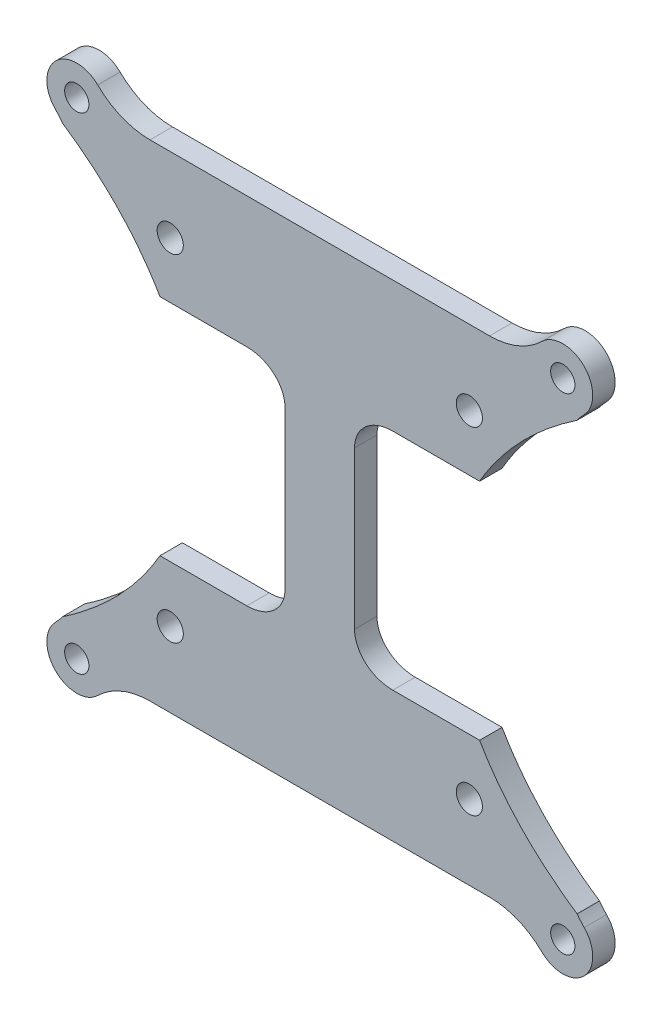
SolidWorks part; units mm, degrees
material "ABS"
ref_plane "Спереди" through (0, 0, 0) normal (0, 0, 1) x (1, 0, 0)
ref_plane "Сверху" through (0, 0, 0) normal (0, 1, 0) x (1, 0, 0)
ref_plane "Справа" through (0, 0, 0) normal (1, 0, 0) x (0, 0, -1)
sketch "Эскиз1" plane through (0, 0, 0) normal (0, 0, 1) x (1, 0, 0)
  line L1 (-32.5, -32.5) -> (32.5, -32.5)
  line L2 (-32.5, -32.5) -> (-32.5, 32.5)
  line L3 (-32.5, 32.5) -> (32.5, 32.5)
  line L4 (32.5, -32.5) -> (32.5, 32.5)
  line L5 (-32.5, -32.5) -> (32.5, 32.5) construction
  line L6 (-32.5, 32.5) -> (32.5, -32.5) construction
  circle A0 centre (-32.5, 32.5) radius 1.625
  arc A1 (-28.5, 32.5) -> (-32.5, 28.5) centre (-32.5, 32.5) ccw
  circle A2 centre (32.5, 32.5) radius 1.625
  arc A3 (32.5, 28.5) -> (28.5, 32.5) centre (32.5, 32.5) ccw
  circle A4 centre (32.5, -32.5) radius 1.625
  arc A5 (28.5, -32.5) -> (32.5, -28.5) centre (32.5, -32.5) ccw
  circle A6 centre (-32.5, -32.5) radius 1.625
  arc A7 (-32.5, -28.5) -> (-28.5, -32.5) centre (-32.5, -32.5) ccw
  point P0 (0, 0)
  point P20 (0, 0)
  dimension "D2" = 3.25
  dimension "D3" = 8
  dimension "D1" = 65
  dimension "D4" = 4
extrude "Бобышка-Вытянуть1" add sketch "Эскиз1" along normal blind 3 contours A6 L1 A4 L4 A2 L3 A0 L2 | L3 A1 L2 A0 | L4 A3 L3 A2 | L1 A5 L4 A4 | L2 A7 L1 A6
fillet "Скругление1" radius 10 8 edges at (-28.5, -32.5, 1.5) (-32.5, -28.5, 1.5) (-28.5, 32.5, 1.5) (-32.5, 28.5, 1.5) (28.5, 32.5, 1.5) (32.5, 28.5, 1.5) (32.5, -28.5, 1.5) (28.5, -32.5, 1.5)
sketch "Эскиз2" plane through (0, 0, 0) normal (0, 0, -1) x (-1, 0, 0)
  line L0 (0, 32.5) -> (0, -32.5) construction
  line L1 (22.702, 32.5) -> (-22.702, 32.5) construction
  line L2 (22.702, -32.5) -> (-22.702, -32.5) construction
  line L3 (-32.5, 22.5) -> (32.5, 22.5) construction
  line L4 (-32.5, -22.702) -> (-32.5, 22.702) construction
  line L5 (32.5, -22.702) -> (32.5, 22.702) construction
  line L6 (-32.5, 0) -> (32.5, 0) construction
  circle A0 centre (-20, 22.5) radius 1.75
  circle A1 centre (20, 22.5) radius 1.75
  circle A2 centre (20, -22.5) radius 1.75
  circle A3 centre (-20, -22.5) radius 1.75
  dimension "D1" = 3.5
  dimension "D2" = 20
  dimension "D3" = 10
extrude "Вырез-Вытянуть1" cut sketch "Эскиз2" against normal blind 10
sketch "Эскиз3" plane through (0, 0, 0) normal (0, 0, -1) x (-1, 0, 0)
  line L0 (40.1734, -19.1012) -> (40.1734, -10.8255)
  line L1 (38.7591, -18.1012) -> (38.7591, -11.8255)
  line L2 (38.7591, -18.1012) -> (40.1734, -19.1012)
  line L3 (40.1734, -10.8255) -> (38.7591, -11.8255)
  line L4 (81.8151, -12.8801) -> (82.0001, -12.7701)
  line L5 (81.993, 12.7739) -> (81.7613, 12.9159)
  line L6 (75.9847, -15.2389) -> (79.1335, -15.9875)
  line L7 (79.1811, 15.9349) -> (75.694, 15.2742)
  line L8 (80.0623, 15.5421) -> (80.9227, 13.8292)
  line L9 (80.9227, -13.8292) -> (80.0272, -15.612)
  line L10 (23.1698, 12) -> (9.7678, 12)
  line L11 (23.1698, -12) -> (9.7678, -12)
  line L12 (68.4576, 34.4102) -> (68.4576, 33.9999)
  line L13 (68.4576, -33.9999) -> (68.4575, -34.4102)
  line L14 (23.5994, 5.6485) -> (23.5994, -5.6485)
  line L15 (7.6464, 10.5) -> (7.6464, -10.5)
  line L16 (7.6464, 10.5) -> (7.6464, -10.5)
  line L17 (23.5994, 5.6485) -> (23.5994, -5.6485)
  line L18 (68.4576, -33.9999) -> (68.4575, -34.4102)
  line L19 (68.4576, 34.4102) -> (68.4576, 33.9999)
  line L20 (23.1698, -12) -> (9.7678, -12)
  line L21 (23.1698, 12) -> (9.7678, 12)
  line L22 (80.9227, -13.8292) -> (80.0272, -15.612)
  line L23 (80.0623, 15.5421) -> (80.9227, 13.8292)
  line L24 (79.1811, 15.9349) -> (75.694, 15.2742)
  line L25 (75.9847, -15.2389) -> (79.1335, -15.9875)
  line L26 (81.993, 12.7739) -> (81.7613, 12.9159)
  line L27 (81.8151, -12.8801) -> (82.0001, -12.7701)
  line L28 (40.1734, -10.8255) -> (38.7591, -11.8255)
  line L29 (38.7591, -18.1012) -> (40.1734, -19.1012)
  line L30 (38.7591, -18.1012) -> (38.7591, -11.8255)
  line L31 (40.1734, -19.1012) -> (40.1734, -10.8255)
  line L32 (-40.1734, 19.1012) -> (-40.1734, 10.8255)
  line L33 (-38.7591, 18.1012) -> (-38.7591, 11.8255)
  line L34 (-38.7591, 18.1012) -> (-40.1734, 19.1012)
  line L35 (-40.1734, 10.8255) -> (-38.7591, 11.8255)
  line L36 (-81.8151, 12.8801) -> (-82.0001, 12.7701)
  line L37 (-81.993, -12.7739) -> (-81.7613, -12.9159)
  line L38 (-75.9847, 15.2389) -> (-79.1335, 15.9875)
  line L39 (-79.1811, -15.9349) -> (-75.694, -15.2742)
  line L40 (-80.0623, -15.5421) -> (-80.9227, -13.8292)
  line L41 (-80.9227, 13.8292) -> (-80.0272, 15.612)
  line L42 (-23.1698, -12) -> (-9.7678, -12)
  line L43 (-23.1698, 12) -> (-9.7678, 12)
  line L44 (-68.4576, -34.4102) -> (-68.4576, -33.9999)
  line L45 (-68.4576, 33.9999) -> (-68.4576, 34.4102)
  line L46 (-23.5994, -5.6485) -> (-23.5994, 5.6485)
  line L47 (-7.6464, -10.5) -> (-7.6464, 10.5)
  line L48 (-7.6464, -10.5) -> (-7.6464, 10.5)
  line L49 (-23.5994, -5.6485) -> (-23.5994, 5.6485)
  line L50 (-68.4576, 33.9999) -> (-68.4576, 34.4102)
  line L51 (-68.4576, -34.4102) -> (-68.4576, -33.9999)
  line L52 (-23.1698, 12) -> (-9.7678, 12)
  line L53 (-23.1698, -12) -> (-9.7678, -12)
  line L54 (-80.9227, 13.8292) -> (-80.0272, 15.612)
  line L55 (-80.0623, -15.5421) -> (-80.9227, -13.8292)
  line L56 (-79.1811, -15.9349) -> (-75.694, -15.2742)
  line L57 (-75.9847, 15.2389) -> (-79.1335, 15.9875)
  line L58 (-81.993, -12.7739) -> (-81.7613, -12.9159)
  line L59 (-81.8151, 12.8801) -> (-82.0001, 12.7701)
  line L60 (-40.1734, 10.8255) -> (-38.7591, 11.8255)
  line L61 (-38.7591, 18.1012) -> (-40.1734, 19.1012)
  line L62 (-38.7591, 18.1012) -> (-38.7591, 11.8255)
  line L63 (-40.1734, 19.1012) -> (-40.1734, 10.8255)
  line L64 (-21.3752, 15) -> (-9.7678, 15)
  line L65 (-4.6464, -10.5) -> (-4.6464, 10.5)
  line L66 (-21.3752, -15) -> (-9.7678, -15)
  line L67 (-71.4576, -34.4101) -> (-71.4576, -31.1169)
  line L68 (-26.5994, -5.2847) -> (-26.5994, 5.2847)
  line L69 (-71.4576, 31.1169) -> (-71.4576, 34.4102)
  line L70 (21.3752, 15) -> (9.7678, 15)
  line L71 (4.6464, 10.5) -> (4.6464, -10.5)
  line L72 (21.3752, -15) -> (9.7678, -15)
  line L73 (71.4587, -31.117) -> (71.4575, -34.4505)
  line L74 (26.5994, 5.2847) -> (26.5994, -5.2847)
  line L75 (71.4576, 34.4109) -> (71.4577, 31.1169)
  spline S0 degree 3 poles (10.4749, -7.5) (10.4749, -3.5) (16.1317, -3.5) (16.1317, -7.5) (16.1317, -11.5) (10.4749, -11.5) (10.4749, -7.5) (10.4749, -3.5) (16.1317, -3.5) knots -0.5 0 0 0 0.5 0.5 0.5 1 1 1 1.5 1.5 1.5 weights 1 0.333333 0.333333 1 0.333333 0.333333 1 0.333333 0.333333 only from (10.4749, -7.5) to (10.4749, -7.5)
  spline S1 degree 3 poles (10.4749, 7.5) (10.4749, 11.5) (16.1317, 11.5) (16.1317, 7.5) (16.1317, 3.5) (10.4749, 3.5) (10.4749, 7.5) (10.4749, 11.5) (16.1317, 11.5) knots -0.5 0 0 0 0.5 0.5 0.5 1 1 1 1.5 1.5 1.5 weights 1 0.333333 0.333333 1 0.333333 0.333333 1 0.333333 0.333333 only from (10.4749, 7.5) to (10.4749, 7.5)
  spline S2 degree 3 poles (75.2786, -15.2354) (75.5104, -15.1829) (75.7539, -15.1841) (75.9847, -15.2389) knots 0 0 0 0 1 1 1 1 weights 1 0.966708 0.966708 1
  spline S3 degree 3 poles (-1611.9841, -2490.4248) (107.8063, 15.4248) (78.9871, -16.9374) (81.0411, -13.6256) (81.1175, -13.5185) (81.2068, -13.4081) (81.3058, -13.2991) (81.4203, -13.1863) (81.5604, -13.0632) (86.0077, -9.7973) (-8.3315, -82.6851) (1958.2049, 2327.5554) knots -7.34165 -7.34165 -7.34165 -7.34165 0.084221 0.176281 0.276186 0.383927 0.499481 0.611478 0.749788 0.924174 8.950699 8.950699 8.950699 8.950699 only from (80.9227, -13.8292) to (81.8151, -12.8801)
  spline S4 degree 3 poles (80.0272, -15.612) (79.8643, -15.9364) (79.5225, -16.08) (79.1335, -15.9875) knots 0 0 0 0 1 1 1 1 weights 1 0.8715 0.8715 1
  spline S5 degree 3 poles (75.694, 15.2742) (75.4864, 15.2349) (75.2715, 15.2378) (75.0662, 15.2828) knots 0 0 0 0 1 1 1 1 weights 1 0.97382 0.97382 1
  spline S6 degree 3 poles (79.1811, 15.9349) (79.5679, 16.0082) (79.9033, 15.8587) (80.0623, 15.5421) knots 0 0 0 0 1 1 1 1 weights 1 0.875797 0.875797 1
  spline S7 degree 3 poles (-1937.5466, -2205.5697) (231.9437, 201.1466) (98.3102, -0.4929) (81.5125, 13.1046) (81.3962, 13.2091) (81.2675, 13.3383) (81.137, 13.4904) (77.3927, 18.8363) (129.5432, -17.5929) (-2030.1695, 2144.6881) knots -51.132511 -51.132511 -51.132511 -51.132511 0.124537 0.249858 0.374039 0.498828 0.686618 0.853684 14.255317 14.255317 14.255317 14.255317 only from (81.7613, 12.9159) to (80.9227, 13.8292)
  spline S8 degree 3 poles (3061.2547, -241.2689) (42.8141, -24.9242) (69.0039, -30.7252) (68.4405, -34.6081) (68.4142, -34.7204) (68.3493, -34.9029) (68.2007, -35.1493) (67.9533, -35.395) (67.6517, -35.5947) (67.3374, -35.7342) (66.9897, -35.8321) (66.6982, -35.8734) (59.3585, -36.2144) (52.2357, -1.2696) (37.4507, -3035.645) knots -3.843288 -3.843288 -3.843288 -3.843288 0.033193 0.06659 0.100333 0.149309 0.261141 0.386702 0.497425 0.623884 0.731384 0.860481 0.9194 8.126573 8.126573 8.126573 8.126573 only from (68.4575, -34.4102) to (66.2132, -35.8754)
  spline S9 degree 3 poles (2878.0258, 1077.9449) (41.8351, -70.8926) (52.2555, 35.5569) (66.4941, 35.8853) (66.7631, 35.8695) (67.1233, 35.8008) (67.4532, 35.6896) (67.7786, 35.5205) (68.0573, 35.3049) (68.248, 35.0751) (68.356, 34.8784) (68.4144, 34.7238) (70.0481, 27.3563) (-5.7355, 46.2982) (1192.6861, -2746.0805) knots -14.151772 -14.151772 -14.151772 -14.151772 0.030465 0.060951 0.191843 0.300888 0.429435 0.541045 0.668884 0.781672 0.839039 0.894208 0.947683 8.134036 8.134036 8.134036 8.134036 only from (66.2131, 35.8754) to (68.4576, 34.4102)
  spline S10 degree 3 poles (7.6464, 10.5) (7.6464, 11.3787) (8.5251, 12) (9.7678, 12) knots 0 0 0 0 1 1 1 1 weights 1 0.804738 0.804738 1
  spline S11 degree 3 poles (9.7678, -12) (8.5251, -12) (7.6464, -11.3787) (7.6464, -10.5) knots 0 0 0 0 1 1 1 1 weights 1 0.804738 0.804738 1
  spline S12 degree 3 poles (66.2132, -35.8754) (45.9554, -34.4336) (29.9459, -25.5534) (23.1698, -12) knots 0 0 0 0 1 1 1 1 weights 1 0.896207 0.896207 1
  spline S13 degree 3 poles (23.1698, 12) (29.9459, 25.5534) (45.9553, 34.4336) (66.2131, 35.8754) knots 0 0 0 0 1 1 1 1 weights 1 0.896207 0.896207 1
  spline S14 degree 3 poles (81.993, 12.7739) (83.2472, 12.105) (84.3964, 11.3476) (85.4284, 10.5101) knots 0 0 0 0 1 1 1 1 weights 1 0.996402 0.996402 1
  spline S15 degree 3 poles (85.4283, -10.5101) (84.3984, -11.3461) (83.2515, -12.1021) (82.0001, -12.7701) knots 0 0 0 0 1 1 1 1 weights 1 0.996415 0.996415 1
  spline S16 degree 3 poles (75.2786, -15.2354) (59.3562, -18.8468) (45.8227, -11.9024) (45.7404, -0.0787) (45.6581, 11.7449) (59.0944, 18.7831) (75.0662, 15.2828) knots 0 0 0 0 0.5 0.5 0.5 1 1 1 1 weights 1 0.727531 0.727531 1 0.727531 0.727531 1
  spline S17 degree 3 poles (-2254.78, 1887.0934) (45.695, 2.1755) (72.5444, 21.8095) (85.9765, 10.0439) (86.2382, 9.8032) (86.4915, 9.5581) (86.9723, 9.0696) (87.637, 8.3075) (88.4098, 7.2278) (89.1848, 5.8925) (89.8783, 4.2706) (90.3804, 2.3398) (90.5866, 0.3596) (90.489, -1.6318) (90.0914, -3.5903) (89.4067, -5.4592) (88.4482, -7.2191) (87.5257, -8.4479) (86.7993, -9.2478) (86.3671, -9.6837) (64.0114, -30.4239) (-61.3644, -10.9521) (1719.0327, 2502.7947) knots -2.166421 -2.166421 -2.166421 -2.166421 0.014985 0.029837 0.044559 0.059151 0.073617 0.129706 0.184548 0.238313 0.321232 0.402799 0.485249 0.567587 0.649509 0.732567 0.813893 0.897623 0.92268 0.948089 0.973859 4.757612 4.757612 4.757612 4.757612 only from (85.4284, 10.5101) to (85.4283, -10.5101)
  spline S18 degree 3 poles (68.4576, 33.9999) (45.0004, 33.0667) (27.4964, 22.0038) (23.5994, 5.6485) knots 0 0 0 0 1 1 1 1 weights 1 0.854251 0.854251 1
  spline S19 degree 3 poles (23.5994, -5.6485) (27.4964, -22.0038) (45.0004, -33.0667) (68.4576, -33.9999) knots 0 0 0 0 1 1 1 1 weights 1 0.854251 0.854251 1
  spline S20 degree 3 poles (23.5994, -5.6485) (27.4964, -22.0038) (45.0004, -33.0667) (68.4576, -33.9999) knots 0 0 0 0 1 1 1 1 weights 1 0.854251 0.854251 1
  spline S21 degree 3 poles (68.4576, 33.9999) (45.0004, 33.0667) (27.4964, 22.0038) (23.5994, 5.6485) knots 0 0 0 0 1 1 1 1 weights 1 0.854251 0.854251 1
  spline S22 degree 3 poles (85.4284, 10.5101) (85.522, 10.434) (85.7058, 10.2811) (85.9765, 10.0439) (86.2382, 9.8032) (86.4915, 9.5581) (86.9723, 9.0696) (87.637, 8.3075) (88.4098, 7.2278) (89.1848, 5.8925) (89.8783, 4.2706) (90.3804, 2.3398) (90.5866, 0.3596) (90.489, -1.6318) (90.0914, -3.5903) (89.4067, -5.4592) (88.4482, -7.2191) (87.5257, -8.4479) (86.7993, -9.2478) (86.3671, -9.6837) (85.9163, -10.1019) (85.5946, -10.3752) (85.4283, -10.5101) knots 0 0 0 0 0.014985 0.029837 0.044559 0.059151 0.073617 0.129706 0.184548 0.238313 0.321232 0.402799 0.485249 0.567587 0.649509 0.732567 0.813893 0.897623 0.92268 0.948089 0.973859 1 1 1 1
  spline S23 degree 3 poles (75.2786, -15.2354) (59.3562, -18.8468) (45.8227, -11.9024) (45.7404, -0.0787) (45.6581, 11.7449) (59.0944, 18.7831) (75.0662, 15.2828) knots 0 0 0 0 0.5 0.5 0.5 1 1 1 1 weights 1 0.727531 0.727531 1 0.727531 0.727531 1
  spline S24 degree 3 poles (85.4283, -10.5101) (84.3984, -11.3461) (83.2515, -12.1021) (82.0001, -12.7701) knots 0 0 0 0 1 1 1 1 weights 1 0.996415 0.996415 1
  spline S25 degree 3 poles (81.993, 12.7739) (83.2472, 12.105) (84.3964, 11.3476) (85.4284, 10.5101) knots 0 0 0 0 1 1 1 1 weights 1 0.996402 0.996402 1
  spline S26 degree 3 poles (23.1698, 12) (29.9459, 25.5534) (45.9553, 34.4336) (66.2131, 35.8754) knots 0 0 0 0 1 1 1 1 weights 1 0.896207 0.896207 1
  spline S27 degree 3 poles (66.2132, -35.8754) (45.9554, -34.4336) (29.9459, -25.5534) (23.1698, -12) knots 0 0 0 0 1 1 1 1 weights 1 0.896207 0.896207 1
  spline S28 degree 3 poles (9.7678, -12) (8.5251, -12) (7.6464, -11.3787) (7.6464, -10.5) knots 0 0 0 0 1 1 1 1 weights 1 0.804738 0.804738 1
  spline S29 degree 3 poles (7.6464, 10.5) (7.6464, 11.3787) (8.5251, 12) (9.7678, 12) knots 0 0 0 0 1 1 1 1 weights 1 0.804738 0.804738 1
  spline S30 degree 3 poles (66.2131, 35.8754) (66.2433, 35.8775) (66.3037, 35.8809) (66.4941, 35.8853) (66.7631, 35.8695) (67.1233, 35.8008) (67.4532, 35.6896) (67.7786, 35.5205) (68.0573, 35.3049) (68.248, 35.0751) (68.356, 34.8784) (68.4144, 34.7238) (68.4504, 34.5612) (68.4576, 34.46) (68.4576, 34.4102) knots 0 0 0 0 0.030465 0.060951 0.191843 0.300888 0.429435 0.541045 0.668884 0.781672 0.839039 0.894208 0.947683 1 1 1 1
  spline S31 degree 3 poles (68.4575, -34.4102) (68.4566, -34.4432) (68.4549, -34.5093) (68.4405, -34.6081) (68.4142, -34.7204) (68.3493, -34.9029) (68.2007, -35.1493) (67.9533, -35.395) (67.6517, -35.5947) (67.3374, -35.7342) (66.9897, -35.8321) (66.6982, -35.8734) (66.4316, -35.8858) (66.2932, -35.8792) (66.2132, -35.8754) knots 0 0 0 0 0.033193 0.06659 0.100333 0.149309 0.261141 0.386702 0.497425 0.623884 0.731384 0.860481 0.9194 1 1 1 1
  spline S32 degree 3 poles (81.7613, 12.9159) (81.7187, 12.945) (81.6344, 13.0059) (81.5125, 13.1046) (81.3962, 13.2091) (81.2675, 13.3383) (81.137, 13.4904) (81.0006, 13.6851) (80.9451, 13.7847) (80.9227, 13.8292) knots 0 0 0 0 0.124537 0.249858 0.374039 0.498828 0.686618 0.853684 1 1 1 1
  spline S33 degree 3 poles (79.1811, 15.9349) (79.5679, 16.0082) (79.9033, 15.8587) (80.0623, 15.5421) knots 0 0 0 0 1 1 1 1 weights 1 0.875797 0.875797 1
  spline S34 degree 3 poles (75.694, 15.2742) (75.4864, 15.2349) (75.2715, 15.2378) (75.0662, 15.2828) knots 0 0 0 0 1 1 1 1 weights 1 0.97382 0.97382 1
  spline S35 degree 3 poles (80.0272, -15.612) (79.8643, -15.9364) (79.5225, -16.08) (79.1335, -15.9875) knots 0 0 0 0 1 1 1 1 weights 1 0.8715 0.8715 1
  spline S36 degree 3 poles (80.9227, -13.8292) (80.936, -13.8027) (80.9666, -13.7456) (81.0411, -13.6256) (81.1175, -13.5185) (81.2068, -13.4081) (81.3058, -13.2991) (81.4203, -13.1863) (81.5604, -13.0632) (81.7676, -12.9111) (81.8092, -12.8839) (81.8151, -12.8801) knots 0 0 0 0 0.084221 0.176281 0.276186 0.383927 0.499481 0.611478 0.749788 0.924174 1 1 1 1
  spline S37 degree 3 poles (75.2786, -15.2354) (75.5104, -15.1829) (75.7539, -15.1841) (75.9847, -15.2389) knots 0 0 0 0 1 1 1 1 weights 1 0.966708 0.966708 1
  spline S38 degree 3 poles (10.4749, 7.5) (10.4749, 11.5) (16.1317, 11.5) (16.1317, 7.5) (16.1317, 3.5) (10.4749, 3.5) (10.4749, 7.5) (10.4749, 11.5) (16.1317, 11.5) knots -0.5 0 0 0 0.5 0.5 0.5 1 1 1 1.5 1.5 1.5 weights 1 0.333333 0.333333 1 0.333333 0.333333 1 0.333333 0.333333 only from (10.4749, 7.5) to (10.4749, 7.5)
  spline S39 degree 3 poles (10.4749, -7.5) (10.4749, -3.5) (16.1317, -3.5) (16.1317, -7.5) (16.1317, -11.5) (10.4749, -11.5) (10.4749, -7.5) (10.4749, -3.5) (16.1317, -3.5) knots -0.5 0 0 0 0.5 0.5 0.5 1 1 1 1.5 1.5 1.5 weights 1 0.333333 0.333333 1 0.333333 0.333333 1 0.333333 0.333333 only from (10.4749, -7.5) to (10.4749, -7.5)
  spline S40 degree 3 poles (-10.4749, 7.5) (-10.4749, 3.5) (-16.1317, 3.5) (-16.1317, 7.5) (-16.1317, 11.5) (-10.4749, 11.5) (-10.4749, 7.5) (-10.4749, 3.5) (-16.1317, 3.5) knots -0.5 0 0 0 0.5 0.5 0.5 1 1 1 1.5 1.5 1.5 weights 1 0.333333 0.333333 1 0.333333 0.333333 1 0.333333 0.333333 only from (-10.4749, 7.5) to (-10.4749, 7.5)
  spline S41 degree 3 poles (-10.4749, -7.5) (-10.4749, -11.5) (-16.1317, -11.5) (-16.1317, -7.5) (-16.1317, -3.5) (-10.4749, -3.5) (-10.4749, -7.5) (-10.4749, -11.5) (-16.1317, -11.5) knots -0.5 0 0 0 0.5 0.5 0.5 1 1 1 1.5 1.5 1.5 weights 1 0.333333 0.333333 1 0.333333 0.333333 1 0.333333 0.333333 only from (-10.4749, -7.5) to (-10.4749, -7.5)
  spline S42 degree 3 poles (-75.2786, 15.2354) (-75.5104, 15.1829) (-75.7539, 15.1841) (-75.9847, 15.2389) knots 0 0 0 0 1 1 1 1 weights 1 0.966708 0.966708 1
  spline S43 degree 3 poles (1611.9872, 2490.4232) (-107.8063, -15.4248) (-78.987, 16.9374) (-81.0411, 13.6256) (-81.1175, 13.5185) (-81.2068, 13.4081) (-81.3058, 13.2991) (-81.4203, 13.1863) (-81.5604, 13.0632) (-86.0077, 9.7973) (8.333, 82.6862) (-1958.2532, -2327.6148) knots -7.341654 -7.341654 -7.341654 -7.341654 0.084221 0.176281 0.276186 0.383927 0.499481 0.611478 0.749788 0.924174 8.950764 8.950764 8.950764 8.950764 only from (-80.9227, 13.8292) to (-81.8151, 12.8801)
  spline S44 degree 3 poles (-80.0272, 15.612) (-79.8643, 15.9364) (-79.5225, 16.08) (-79.1335, 15.9875) knots 0 0 0 0 1 1 1 1 weights 1 0.8715 0.8715 1
  spline S45 degree 3 poles (-75.694, -15.2742) (-75.4864, -15.2349) (-75.2715, -15.2378) (-75.0662, -15.2828) knots 0 0 0 0 1 1 1 1 weights 1 0.97382 0.97382 1
  spline S46 degree 3 poles (-79.1811, -15.9349) (-79.5679, -16.0082) (-79.9033, -15.8587) (-80.0623, -15.5421) knots 0 0 0 0 1 1 1 1 weights 1 0.875797 0.875797 1
  spline S47 degree 3 poles (1937.5466, 2205.5697) (-231.9437, -201.1466) (-98.3102, 0.4929) (-81.5125, -13.1046) (-81.3962, -13.2091) (-81.2675, -13.3383) (-81.137, -13.4904) (-77.3927, -18.8363) (-129.5432, 17.5929) (2030.1695, -2144.6881) knots -51.132511 -51.132511 -51.132511 -51.132511 0.124537 0.249858 0.374039 0.498828 0.686618 0.853684 14.255317 14.255317 14.255317 14.255317 only from (-81.7613, -12.9159) to (-80.9227, -13.8292)
  spline S48 degree 3 poles (-3066.1338, -24.4044) (-33.637, -31.5294) (-64.9074, -36.0132) (-66.6934, -35.8767) (-67.1624, -35.7998) (-67.6079, -35.6348) (-67.9987, -35.3577) (-68.2464, -35.0892) (-68.4137, -34.7756) (-68.9245, -31.8511) (-58.4455, -33.2368) (-828.9561, 2867.4048) knots -2.395784 -2.395784 -2.395784 -2.395784 0.035741 0.172478 0.275349 0.514926 0.642895 0.755601 0.88057 0.996324 3.633178 3.633178 3.633178 3.633178 only from (-66.2132, -35.8754) to (-68.4576, -34.4102)
  spline S49 degree 3 poles (-1571.0486, -2561.988) (-67.1744, 32.7038) (-68.6613, 33.6145) (-68.3988, 34.8283) (-68.1289, 35.262) (-67.6406, 35.6348) (-66.9563, 35.8627) (-64.9671, 36.036) (-53.6432, 33.1774) (-3062.4904, -110.3637) knots -0.938051 -0.938051 -0.938051 -0.938051 0.00005 0.148857 0.270885 0.510832 0.751134 0.991618 2.927544 2.927544 2.927544 2.927544 only from (-68.4576, 34.4102) to (-66.2132, 35.8754)
  spline S50 degree 3 poles (-7.6464, -10.5) (-7.6464, -11.3787) (-8.5251, -12) (-9.7678, -12) knots 0 0 0 0 1 1 1 1 weights 1 0.804738 0.804738 1
  spline S51 degree 3 poles (-9.7678, 12) (-8.5251, 12) (-7.6464, 11.3787) (-7.6464, 10.5) knots 0 0 0 0 1 1 1 1 weights 1 0.804738 0.804738 1
  spline S52 degree 3 poles (-66.2132, 35.8754) (-45.9554, 34.4336) (-29.9459, 25.5534) (-23.1698, 12) knots 0 0 0 0 1 1 1 1 weights 1 0.896207 0.896207 1
  spline S53 degree 3 poles (-23.1698, -12) (-29.9459, -25.5534) (-45.9554, -34.4336) (-66.2132, -35.8754) knots 0 0 0 0 1 1 1 1 weights 1 0.896207 0.896207 1
  spline S54 degree 3 poles (-81.993, -12.7739) (-83.2472, -12.105) (-84.3964, -11.3476) (-85.4284, -10.5101) knots 0 0 0 0 1 1 1 1 weights 1 0.996402 0.996402 1
  spline S55 degree 3 poles (-85.4283, 10.5101) (-84.3984, 11.3461) (-83.2515, 12.1021) (-82.0001, 12.7701) knots 0 0 0 0 1 1 1 1 weights 1 0.996415 0.996415 1
  spline S56 degree 3 poles (-75.2786, 15.2354) (-59.3562, 18.8468) (-45.8227, 11.9024) (-45.7404, 0.0787) (-45.6581, -11.7449) (-59.0944, -18.7831) (-75.0662, -15.2828) knots 0 0 0 0 0.5 0.5 0.5 1 1 1 1 weights 1 0.727531 0.727531 1 0.727531 0.727531 1
  spline S57 degree 3 poles (2254.78, -1887.0934) (-45.695, -2.1755) (-72.5444, -21.8095) (-85.9765, -10.0439) (-86.2382, -9.8032) (-86.4915, -9.5581) (-86.9723, -9.0696) (-87.637, -8.3075) (-88.4098, -7.2278) (-89.1848, -5.8925) (-89.8783, -4.2706) (-90.3804, -2.3398) (-90.5866, -0.3596) (-90.489, 1.6318) (-90.0914, 3.5903) (-89.4067, 5.4592) (-88.4482, 7.2191) (-87.5257, 8.4479) (-86.7993, 9.2478) (-86.3671, 9.6837) (-64.0114, 30.4239) (61.3644, 10.9521) (-1719.0327, -2502.7947) knots -2.166421 -2.166421 -2.166421 -2.166421 0.014985 0.029837 0.044559 0.059151 0.073617 0.129706 0.184548 0.238313 0.321232 0.402799 0.485249 0.567587 0.649509 0.732567 0.813893 0.897623 0.92268 0.948089 0.973859 4.757612 4.757612 4.757612 4.757612 only from (-85.4284, -10.5101) to (-85.4283, 10.5101)
  spline S58 degree 3 poles (-68.4576, -33.9999) (-45.0004, -33.0667) (-27.4964, -22.0038) (-23.5994, -5.6485) knots 0 0 0 0 1 1 1 1 weights 1 0.854251 0.854251 1
  spline S59 degree 3 poles (-23.5994, 5.6485) (-27.4964, 22.0038) (-45.0004, 33.0667) (-68.4576, 33.9999) knots 0 0 0 0 1 1 1 1 weights 1 0.854251 0.854251 1
  spline S60 degree 3 poles (-23.5994, 5.6485) (-27.4964, 22.0038) (-45.0004, 33.0667) (-68.4576, 33.9999) knots 0 0 0 0 1 1 1 1 weights 1 0.854251 0.854251 1
  spline S61 degree 3 poles (-68.4576, -33.9999) (-45.0004, -33.0667) (-27.4964, -22.0038) (-23.5994, -5.6485) knots 0 0 0 0 1 1 1 1 weights 1 0.854251 0.854251 1
  spline S62 degree 3 poles (-85.4284, -10.5101) (-85.522, -10.434) (-85.7058, -10.2811) (-85.9765, -10.0439) (-86.2382, -9.8032) (-86.4915, -9.5581) (-86.9723, -9.0696) (-87.637, -8.3075) (-88.4098, -7.2278) (-89.1848, -5.8925) (-89.8783, -4.2706) (-90.3804, -2.3398) (-90.5866, -0.3596) (-90.489, 1.6318) (-90.0914, 3.5903) (-89.4067, 5.4592) (-88.4482, 7.2191) (-87.5257, 8.4479) (-86.7993, 9.2478) (-86.3671, 9.6837) (-85.9163, 10.1019) (-85.5946, 10.3752) (-85.4283, 10.5101) knots 0 0 0 0 0.014985 0.029837 0.044559 0.059151 0.073617 0.129706 0.184548 0.238313 0.321232 0.402799 0.485249 0.567587 0.649509 0.732567 0.813893 0.897623 0.92268 0.948089 0.973859 1 1 1 1
  spline S63 degree 3 poles (-75.2786, 15.2354) (-59.3562, 18.8468) (-45.8227, 11.9024) (-45.7404, 0.0787) (-45.6581, -11.7449) (-59.0944, -18.7831) (-75.0662, -15.2828) knots 0 0 0 0 0.5 0.5 0.5 1 1 1 1 weights 1 0.727531 0.727531 1 0.727531 0.727531 1
  spline S64 degree 3 poles (-85.4283, 10.5101) (-84.3984, 11.3461) (-83.2515, 12.1021) (-82.0001, 12.7701) knots 0 0 0 0 1 1 1 1 weights 1 0.996415 0.996415 1
  spline S65 degree 3 poles (-81.993, -12.7739) (-83.2472, -12.105) (-84.3964, -11.3476) (-85.4284, -10.5101) knots 0 0 0 0 1 1 1 1 weights 1 0.996402 0.996402 1
  spline S66 degree 3 poles (-23.1698, -12) (-29.9459, -25.5534) (-45.9554, -34.4336) (-66.2132, -35.8754) knots 0 0 0 0 1 1 1 1 weights 1 0.896207 0.896207 1
  spline S67 degree 3 poles (-66.2132, 35.8754) (-45.9554, 34.4336) (-29.9459, 25.5534) (-23.1698, 12) knots 0 0 0 0 1 1 1 1 weights 1 0.896207 0.896207 1
  spline S68 degree 3 poles (-9.7678, 12) (-8.5251, 12) (-7.6464, 11.3787) (-7.6464, 10.5) knots 0 0 0 0 1 1 1 1 weights 1 0.804738 0.804738 1
  spline S69 degree 3 poles (-7.6464, -10.5) (-7.6464, -11.3787) (-8.5251, -12) (-9.7678, -12) knots 0 0 0 0 1 1 1 1 weights 1 0.804738 0.804738 1
  spline S70 degree 3 poles (-68.4576, 34.4102) (-68.4576, 34.4102) (-68.4576, 34.5563) (-68.3988, 34.8283) (-68.1289, 35.262) (-67.6406, 35.6348) (-66.9563, 35.8627) (-66.5537, 35.8978) (-66.2242, 35.8762) (-66.2132, 35.8754) knots 0 0 0 0 0.00005 0.148857 0.270885 0.510832 0.751134 0.991618 1 1 1 1
  spline S71 degree 3 poles (-66.2132, -35.8754) (-66.2607, -35.8788) (-66.5093, -35.8908) (-66.6934, -35.8767) (-67.1624, -35.7998) (-67.6079, -35.6348) (-67.9987, -35.3577) (-68.2464, -35.0892) (-68.4137, -34.7756) (-68.4571, -34.5272) (-68.4576, -34.4137) (-68.4576, -34.4102) knots 0 0 0 0 0.035741 0.172478 0.275349 0.514926 0.642895 0.755601 0.88057 0.996324 1 1 1 1
  spline S72 degree 3 poles (-81.7613, -12.9159) (-81.7187, -12.945) (-81.6344, -13.0059) (-81.5125, -13.1046) (-81.3962, -13.2091) (-81.2675, -13.3383) (-81.137, -13.4904) (-81.0006, -13.6851) (-80.9451, -13.7847) (-80.9227, -13.8292) knots 0 0 0 0 0.124537 0.249858 0.374039 0.498828 0.686618 0.853684 1 1 1 1
  spline S73 degree 3 poles (-79.1811, -15.9349) (-79.5679, -16.0082) (-79.9033, -15.8587) (-80.0623, -15.5421) knots 0 0 0 0 1 1 1 1 weights 1 0.875797 0.875797 1
  spline S74 degree 3 poles (-75.694, -15.2742) (-75.4864, -15.2349) (-75.2715, -15.2378) (-75.0662, -15.2828) knots 0 0 0 0 1 1 1 1 weights 1 0.97382 0.97382 1
  spline S75 degree 3 poles (-80.0272, 15.612) (-79.8643, 15.9364) (-79.5225, 16.08) (-79.1335, 15.9875) knots 0 0 0 0 1 1 1 1 weights 1 0.8715 0.8715 1
  spline S76 degree 3 poles (-80.9227, 13.8292) (-80.936, 13.8027) (-80.9666, 13.7456) (-81.0411, 13.6256) (-81.1175, 13.5185) (-81.2068, 13.4081) (-81.3058, 13.2991) (-81.4203, 13.1863) (-81.5604, 13.0632) (-81.7676, 12.9111) (-81.8092, 12.8839) (-81.8151, 12.8801) knots 0 0 0 0 0.084221 0.176281 0.276186 0.383927 0.499481 0.611478 0.749788 0.924174 1 1 1 1
  spline S77 degree 3 poles (-75.2786, 15.2354) (-75.5104, 15.1829) (-75.7539, 15.1841) (-75.9847, 15.2389) knots 0 0 0 0 1 1 1 1 weights 1 0.966708 0.966708 1
  spline S78 degree 3 poles (-10.4749, -7.5) (-10.4749, -11.5) (-16.1317, -11.5) (-16.1317, -7.5) (-16.1317, -3.5) (-10.4749, -3.5) (-10.4749, -7.5) (-10.4749, -11.5) (-16.1317, -11.5) knots -0.5 0 0 0 0.5 0.5 0.5 1 1 1 1.5 1.5 1.5 weights 1 0.333333 0.333333 1 0.333333 0.333333 1 0.333333 0.333333 only from (-10.4749, -7.5) to (-10.4749, -7.5)
  spline S79 degree 3 poles (-10.4749, 7.5) (-10.4749, 3.5) (-16.1317, 3.5) (-16.1317, 7.5) (-16.1317, 11.5) (-10.4749, 11.5) (-10.4749, 7.5) (-10.4749, 3.5) (-16.1317, 3.5) knots -0.5 0 0 0 0.5 0.5 0.5 1 1 1 1.5 1.5 1.5 weights 1 0.333333 0.333333 1 0.333333 0.333333 1 0.333333 0.333333 only from (-10.4749, 7.5) to (-10.4749, 7.5)
  spline S80 degree 1 poles (-9.7678, 15) (-4.6464, 10.5) knots 0 0 1 1 construction
  spline S81 degree 1 poles (-4.6464, -10.5) (-9.7678, -15) knots 0 0 1 1 construction
  spline S82 degree 1 poles (-21.3752, -15) (-66.0003, -38.8678) knots 0 0 1 1 construction
  spline S83 degree 1 poles (-66.0002, -38.8678) (-71.4576, -34.4101) knots 0 0 1 1 construction
  spline S84 degree 1 poles (-71.4576, -31.1169) (-26.5994, -5.2847) knots 0 0 1 1 construction
  spline S85 degree 1 poles (-26.5994, 5.2847) (-71.4576, 31.1169) knots 0 0 1 1 construction
  spline S86 degree 1 poles (-71.4576, 34.4102) (-66.0002, 38.8678) knots 0 0 1 1 construction
  spline S87 degree 1 poles (-66.0002, 38.8678) (-21.3752, 15) knots 0 0 1 1 construction
  spline S88 degree 3 poles (-9.7678, 15) (-9.5088, 15) (-9.0033, 14.969) (-7.9063, 14.752) (-6.4997, 14.1416) (-5.0277, 12.6204) (-4.6464, 11.1955) (-4.6464, 10.5) knots 0 0 0 0 0.125 0.25 0.5 0.75 1 1 1 1
  spline S89 degree 3 poles (-4.6464, -10.5) (-4.6464, -11.1955) (-5.0277, -12.6204) (-6.4997, -14.1416) (-7.9063, -14.752) (-9.0033, -14.969) (-9.5088, -15) (-9.7678, -15) knots 0 0 0 0 0.25 0.5 0.75 0.875 1 1 1 1
  spline S90 degree 3 poles (-21.3752, -15) (-21.8372, -15.807) (-22.8151, -17.3663) (-25.1101, -20.4617) (-28.5486, -24.1421) (-33.5353, -28.1546) (-39.2593, -31.6373) (-45.5625, -34.5007) (-52.2583, -36.6859) (-57.9942, -37.9239) (-62.5905, -38.5732) (-64.859, -38.7866) (-66.0003, -38.8678) knots 0.041507 0.041507 0.041507 0.041507 0.101413 0.161318 0.28113 0.400942 0.520753 0.640565 0.760377 0.880188 0.940094 1 1 1 1
  spline S91 degree 3 poles (-66.0002, -38.8678) (-66.075, -38.8732) (-66.2324, -38.881) (-66.4859, -38.8884) (-67.0561, -38.8654) (-67.3818, -38.8096) (-67.919, -38.6911) (-68.4389, -38.5289) (-69.1033, -38.2395) (-69.8926, -37.7129) (-70.6516, -36.9474) (-71.1817, -35.9977) (-71.4135, -35.1245) (-71.4576, -34.6456) (-71.4576, -34.4101) knots 0.000002 0.000002 0.000002 0.000002 0.031251 0.0625 0.124999 0.249997 0.312495 0.374994 0.499992 0.624989 0.749987 0.874985 0.937483 0.999982 0.999982 0.999982 0.999982
  spline S92 degree 3 poles (-71.4576, -31.1169) (-70.807, -31.091) (-69.8363, -31.0517) (-68.5214, -31.0014) (-67.2917, -30.9441) (-65.7107, -30.8341) (-61.913, -30.4585) (-56.1314, -29.4491) (-48.6472, -27.1004) (-41.7938, -23.7968) (-35.951, -19.6978) (-32.1499, -15.8283) (-29.8041, -12.6019) (-28.3902, -10.155) (-27.308, -7.6931) (-26.8083, -6.1049) (-26.5994, -5.2847) knots -0.04792 -0.04792 -0.04792 -0.04792 -0.015453 0.00078 0.017014 0.049481 0.081948 0.211817 0.341685 0.471553 0.601422 0.73129 0.796224 0.861159 0.926093 0.991027 0.991027 0.991027 0.991027
  spline S93 degree 3 poles (-26.5994, 5.2847) (-26.8083, 6.1049) (-27.308, 7.6931) (-28.3902, 10.155) (-29.8041, 12.6019) (-32.1499, 15.8283) (-35.951, 19.6978) (-41.7938, 23.7968) (-48.6472, 27.1004) (-56.1314, 29.4491) (-61.913, 30.4585) (-65.7107, 30.8341) (-67.2917, 30.9441) (-68.5214, 31.0014) (-69.8363, 31.0517) (-70.807, 31.091) (-71.4576, 31.1169) knots 0.008973 0.008973 0.008973 0.008973 0.073907 0.138841 0.203776 0.26871 0.398578 0.528447 0.658315 0.788183 0.918052 0.950519 0.982986 0.99922 1.015453 1.04792 1.04792 1.04792 1.04792
  spline S94 degree 3 poles (-71.4576, 34.4102) (-71.4576, 34.6474) (-71.4124, 35.1322) (-71.1816, 35.9966) (-70.6499, 36.9501) (-69.8939, 37.7115) (-69.099, 38.2426) (-68.3136, 38.58) (-67.4187, 38.8433) (-66.5397, 38.9062) (-66.0002, 38.8678) knots 0 0 0 0 0.0625 0.125 0.25 0.375 0.5 0.625 0.75 1 1 1 1
  spline S95 degree 3 poles (-66.0002, 38.8678) (-64.859, 38.7866) (-62.5905, 38.5732) (-57.9942, 37.9239) (-52.2583, 36.6859) (-45.5625, 34.5007) (-39.2593, 31.6372) (-33.5353, 28.1546) (-28.5486, 24.1421) (-25.1101, 20.4617) (-22.8151, 17.3663) (-21.8372, 15.807) (-21.3752, 15) knots 0 0 0 0 0.059906 0.119812 0.239623 0.359435 0.479247 0.599058 0.71887 0.838682 0.898587 0.958493 0.958493 0.958493 0.958493
  spline S96 degree 1 poles (4.6464, 10.5) (9.7678, 15) knots 0 0 1 1 construction
  spline S97 degree 1 poles (9.7678, -15) (4.6464, -10.5) knots 0 0 1 1 construction
  spline S98 degree 1 poles (66.0355, -38.8703) (21.3752, -15) knots 0 0 1 1 construction
  spline S99 degree 1 poles (71.4575, -34.4505) (66.0355, -38.8703) knots 0 0 1 1 construction
  spline S100 degree 1 poles (26.5994, -5.2847) (71.4587, -31.117) knots 0 0 1 1 construction
  spline S101 degree 1 poles (71.4577, 31.1169) (26.5994, 5.2847) knots 0 0 1 1 construction
  spline S102 degree 1 poles (66.0001, 38.8678) (71.4576, 34.4109) knots 0 0 1 1 construction
  spline S103 degree 1 poles (21.3752, 15) (66.0001, 38.8678) knots 0 0 1 1 construction
  spline S104 degree 3 poles (9.7678, 15) (9.5088, 15) (9.0033, 14.969) (7.9063, 14.752) (6.4997, 14.1416) (5.0277, 12.6204) (4.6464, 11.1955) (4.6464, 10.5) knots 0 0 0 0 0.125 0.25 0.5 0.75 1 1 1 1
  spline S105 degree 3 poles (4.6464, -10.5) (4.6464, -11.1955) (5.0277, -12.6204) (6.4997, -14.1416) (7.9063, -14.752) (9.0033, -14.969) (9.5088, -15) (9.7678, -15) knots 0 0 0 0 0.25 0.5 0.75 0.875 1 1 1 1
  spline S106 degree 3 poles (21.3752, -15) (21.8376, -15.8076) (22.8161, -17.3679) (25.113, -20.4653) (28.5546, -24.1479) (33.546, -28.1623) (39.2755, -31.646) (45.5845, -34.5094) (52.286, -36.6936) (58.0258, -37.9296) (62.6258, -38.5776) (64.8942, -38.7891) (66.0355, -38.8703) knots -0.000648 -0.000648 -0.000648 -0.000648 0.059298 0.119244 0.239137 0.35903 0.478922 0.598815 0.718708 0.838601 0.898547 0.958493 0.958493 0.958493 0.958493
  spline S107 degree 3 poles (66.0355, -38.8703) (66.0707, -38.872) (66.1299, -38.8748) (66.3374, -38.884) (66.7297, -38.8803) (67.0968, -38.8467) (67.6266, -38.7676) (68.2948, -38.592) (69.1039, -38.2397) (69.9165, -37.6982) (70.568, -37.0214) (71.0068, -36.3122) (71.2286, -35.7959) (71.3559, -35.3313) (71.4201, -35.0157) (71.4541, -34.6203) (71.4562, -34.4885) (71.457, -34.4669) (71.4575, -34.4505) knots -0.013162 -0.013162 -0.013162 -0.013162 0.01887 0.050903 0.114968 0.179033 0.243098 0.371228 0.499359 0.627489 0.755619 0.819684 0.88375 0.915782 0.947815 0.979847 0.995864 1.01188 1.01188 1.01188 1.01188
  spline S108 degree 3 poles (71.4587, -31.117) (70.8081, -31.0911) (69.8374, -31.0517) (68.5223, -31.0014) (67.2927, -30.9442) (65.7117, -30.8342) (61.9139, -30.4586) (56.1321, -29.4493) (48.6478, -27.1006) (41.7942, -23.797) (35.9512, -19.698) (32.1501, -15.8285) (29.8042, -12.602) (28.3903, -10.1551) (27.3081, -7.6931) (26.8083, -6.105) (26.5994, -5.2847) knots 0.008973 0.008973 0.008973 0.008973 0.041441 0.057674 0.073908 0.106376 0.138844 0.268714 0.398585 0.528455 0.658326 0.788197 0.853132 0.918067 0.983003 1.047938 1.047938 1.047938 1.047938
  spline S109 degree 3 poles (26.5994, 5.2847) (26.8083, 6.1049) (27.308, 7.6931) (28.3902, 10.155) (29.8041, 12.6019) (32.1499, 15.8284) (35.951, 19.6978) (41.7939, 23.7968) (48.6472, 27.1004) (56.1315, 29.4491) (61.9131, 30.4585) (65.7108, 30.8341) (67.2918, 30.9442) (68.5215, 31.0014) (69.8364, 31.0517) (70.8072, 31.091) (71.4577, 31.1169) knots -0.047922 -0.047922 -0.047922 -0.047922 0.017012 0.081946 0.146881 0.211815 0.341684 0.471552 0.601421 0.73129 0.861158 0.893626 0.926093 0.942326 0.95856 0.991027 0.991027 0.991027 0.991027
  spline S110 degree 3 poles (71.4576, 34.4109) (71.4574, 34.8697) (71.2883, 35.8168) (70.6531, 36.9419) (69.8964, 37.7114) (68.8347, 38.4164) (67.5224, 38.847) (66.5103, 38.9041) (66.0001, 38.8678) knots 0.000002 0.000002 0.000002 0.000002 0.125028 0.250054 0.37508 0.500105 0.750157 1.000208 1.000208 1.000208 1.000208
  spline S111 degree 3 poles (66.0001, 38.8678) (64.8589, 38.7866) (62.5904, 38.5732) (57.9941, 37.9239) (52.2582, 36.6859) (45.5625, 34.5007) (39.2593, 31.6372) (33.5352, 28.1546) (28.5485, 24.1421) (25.1101, 20.4616) (22.8151, 17.3663) (21.8372, 15.807) (21.3752, 15) knots 0.041507 0.041507 0.041507 0.041507 0.101413 0.161318 0.28113 0.400942 0.520753 0.640565 0.760377 0.880188 0.940094 1 1 1 1
  arc M6 (35.3571, -29.7006) -> (32.5, -22.702) centre (42.5, -22.702) cw
  arc M8 (32.5, 22.702) -> (35.3571, 29.7006) centre (42.5, 22.702) cw
  arc M14 (-35.3571, 29.7006) -> (-32.5, 22.702) centre (-42.5, 22.702) cw
  arc M16 (-32.5, -22.702) -> (-35.3571, -29.7006) centre (-42.5, -22.702) cw
  dimension "D1" = 3
extrude "Вырез-Вытянуть2" cut sketch "Эскиз3" against normal blind 10 contours S95 S67 L52 S68 L48 S69 L53 S66 S90 L66 S89 L65 S88 L64 M14 M16 | S111 L70 S104 L71 S105 L72 S106 S27 L20 S28 L16 S29 L21 S26 M8 M6
